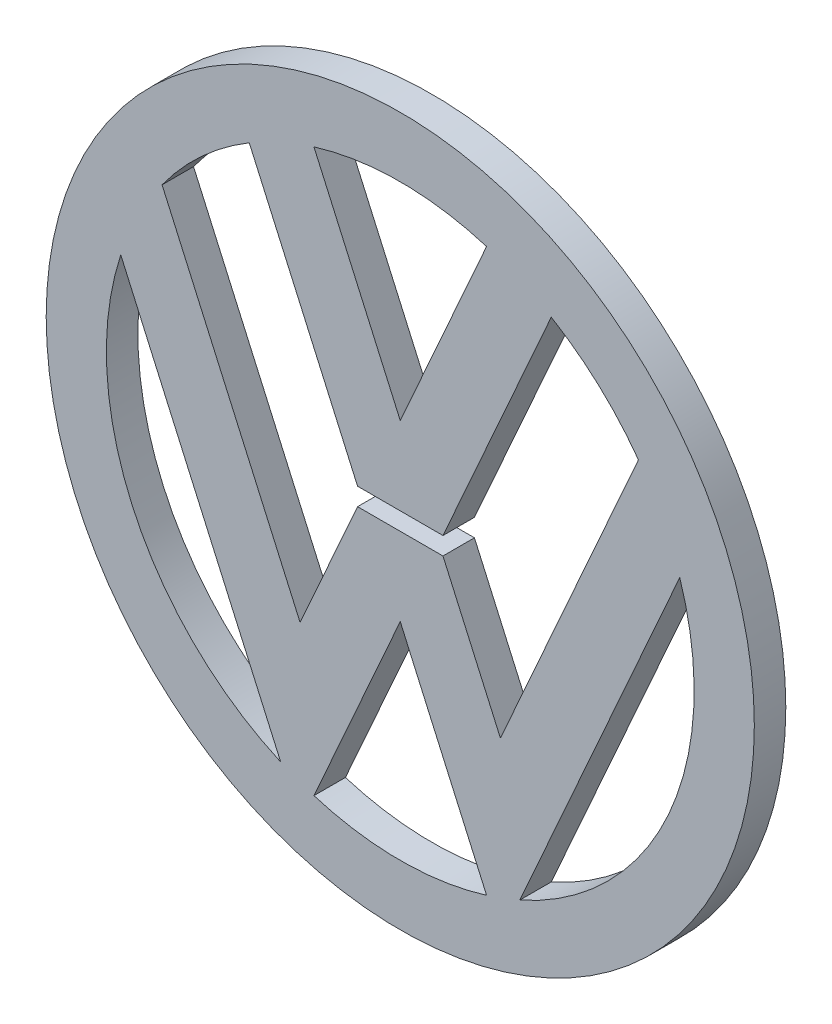
SolidWorks part; units mm, degrees
ref_plane "Front Plane" through (0, 0, 0) normal (0, 0, 1) x (1, 0, 0)
ref_plane "Top Plane" through (0, 0, 0) normal (0, 1, 0) x (1, 0, 0)
ref_plane "Right Plane" through (0, 0, 0) normal (1, 0, 0) x (0, 0, -1)
sketch "Sketch1" plane through (0, 0, 0) normal (0, 0, 1) x (1, 0, 0)
  line L0 (-13.4555, 30.2216) -> (13.4555, -30.2216) construction
  line L1 (13.4555, 30.2216) -> (-13.4555, -30.2216) construction
  line L2 (0, 30.1122) -> (0, -30.2216) construction
  line L3 (-19.1919, 32.0421) -> (-4.9259, 0) construction
  line L4 (-10.97, 35.7027) -> (0, 11.0637)
  line L5 (10.97, 35.7027) -> (-2.4629, 5.5318) construction
  line L6 (-10.97, -35.7027) -> (0, -11.0637)
  line L7 (-35.522, 11.5418) -> (-15.1916, -34.1209)
  line L8 (-30.272, 21.8776) -> (-12.7287, -17.5254)
  line L9 (12.7287, -17.5254) -> (30.272, 21.8776)
  line L10 (35.522, 11.5418) -> (15.1916, -34.1209)
  line L11 (-29.3366, -2.3507) -> (-21.1147, 1.31) construction
  line L12 (15.5623, -11.161) -> (23.7842, -14.8217) construction
  line L13 (3.2323, 18.3236) -> (11.4543, 14.663) construction
  line L14 (-11.1969, 14.085) -> (-2.975, 17.7456) construction
  line L15 (4.9259, 0) -> (12.7287, -17.5254) construction
  line L16 (4.9259, 0) -> (19.1919, 32.0421) construction
  line L17 (-4.9259, 0) -> (-12.7287, -17.5254) construction
  line L18 (-2.4629, -5.5318) -> (10.97, -35.7027) construction
  line L19 (0, 11.0637) -> (10.97, 35.7027)
  line L20 (0, -11.0637) -> (10.97, -35.7027)
  line L21 (-5.4267, -1.125) -> (-12.7287, -17.5254)
  line L22 (-5.4267, 1.125) -> (5.4267, 1.125)
  line L23 (-5.4267, 1.125) -> (-5.4267, -1.125) construction
  line L24 (-5.4267, -1.125) -> (5.4267, -1.125)
  line L25 (5.4267, 1.125) -> (5.4267, -1.125) construction
  line L26 (-5.4267, 1.125) -> (5.4267, -1.125) construction
  line L27 (-5.4267, -1.125) -> (5.4267, 1.125) construction
  line L28 (-5.4267, 1.125) -> (-19.1919, 32.0421)
  line L29 (5.4267, 1.125) -> (19.1919, 32.0421)
  line L30 (5.4267, -1.125) -> (12.7287, -17.5254)
  circle A0 centre (0, 0) radius 45
  arc A1 (-35.522, 11.5418) -> (-15.1916, -34.1209) centre (0, 0) ccw
  arc A2 (30.272, 21.8776) -> (19.1919, 32.0421) centre (0, 0) ccw
  arc A3 (10.97, 35.7027) -> (-10.97, 35.7027) centre (0, 0) ccw
  arc A4 (-19.1919, 32.0421) -> (-30.272, 21.8776) centre (0, 0) ccw
  arc A5 (-10.97, -35.7027) -> (10.97, -35.7027) centre (0, 0) ccw
  arc A6 (15.1916, -34.1209) -> (35.522, 11.5418) centre (0, 0) ccw
  point P9 (0, 0)
  point P20 (15.1916, -34.1209)
  point P33 (-7.0859, 15.9153)
  point P34 (7.3433, 16.4933)
  point P43 (-15.1916, -34.1209)
  dimension "diameter" = 90
  dimension "D1" = 7.65
  dimension "D2" = 24
  dimension "D3" = 24
  dimension "D4" = 9
  dimension "D5" = 2.25
extrude "Boss-Extrude1" add sketch "Sketch1" along normal blind 4
equation "\"D\"= 90"
equation "\"diameter@Sketch1\"=\"D\""
equation "\"D1@Sketch1\"=\"D\"*0.085"
equation "\"D4@Sketch1\"=\"D\"*0.1"
equation "\"D5@Sketch1\"=\"D\"*0.025"
